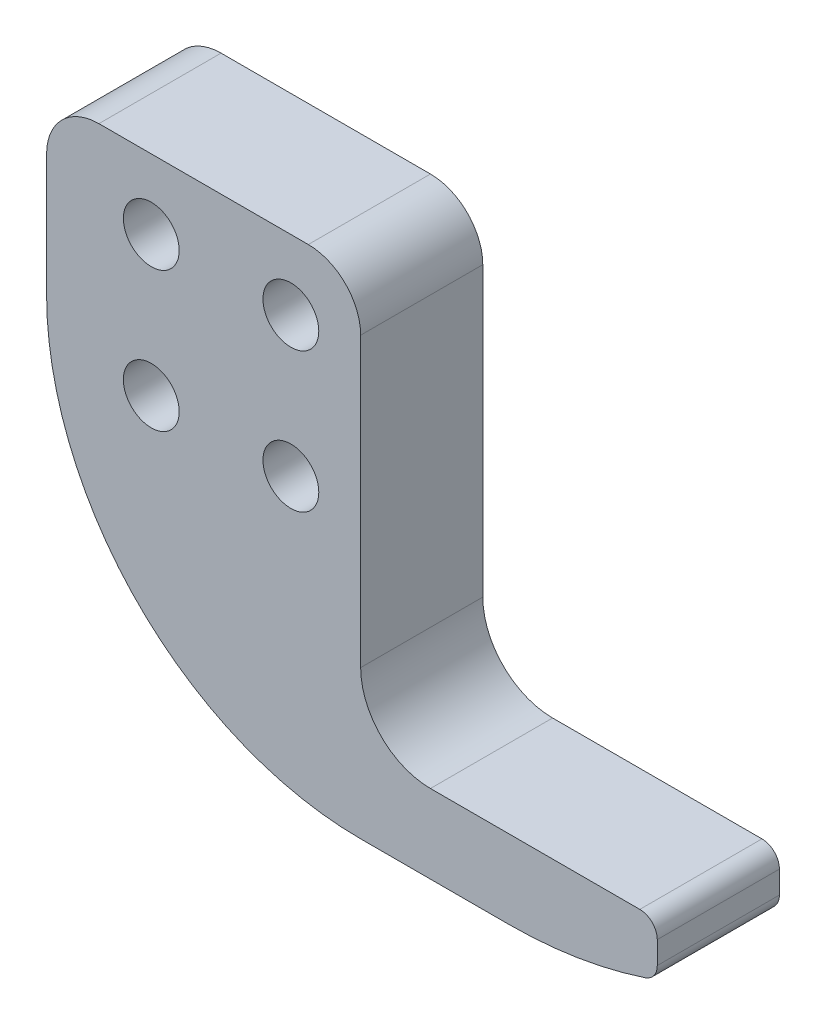
SolidWorks part; units mm, degrees
material "光敏树脂"
ref_plane "前视基准面" through (0, 0, 0) normal (0, 0, 1) x (1, 0, 0)
ref_plane "上视基准面" through (0, 0, 0) normal (0, 1, 0) x (1, 0, 0)
ref_plane "右视基准面" through (0, 0, 0) normal (1, 0, 0) x (0, 0, -1)
sketch "草图1" plane through (0, 0, 0) normal (0, 0, 1) x (1, 0, 0)
  line L0 (-139.1546, 76.5) -> (-139.1546, -33.6254) construction
  line L1 (-91.6495, 50) -> (0, 50) construction
  line L2 (-90.2793, 53) -> (-5.3283, 53) construction
  line L4 (-99.1546, 26.5) -> (0, 26.5) construction
  line L6 (-99.1546, 26.5) -> (-88, 26.5) construction
  line L7 (0, 26.5) -> (0, 0) construction
  line L8 (-88, 26.5) -> (-88, -20.8435) construction
  arc A0 (-139.1546, 66.5) -> (-99.1546, 26.5) centre (-99.1546, 66.5) ccw
  dimension "D1" = 3
  dimension "D4" = 80
  dimension "D3" = 23.5
  dimension "D7" = 10
  dimension "D8" = 88
  dimension "D9" = 11.1546
sketch "草图2" plane through (0, 0, 0) normal (0, 0, 1) x (1, 0, 0)
  line L0 (0, 0) -> (-88, 0) construction
  line L1 (-88, 26.5) -> (-88, -20.8435) construction
  line L2 (0, 3) -> (-88, 3) construction
  line L3 (-99.1546, 26.5) -> (0, 26.5) construction
  line L4 (-139.1546, 76.5) -> (-139.1546, -33.6254) construction
  line L5 (-99.1546, 26.5) -> (-88, 26.5) construction
  line L6 (-139.1546, 76.5) -> (-139.1546, 66.5) construction
  line L7 (-88, 3) -> (-88, 26.5) construction
  line L8 (-161.1546, 76.5) -> (-161.1546, 66.5) construction
  line L9 (-99.1546, 4.5) -> (-88, 4.5) construction
  line L10 (-117.1546, 76.5) -> (-117.1546, 66.5)
  line L11 (-99.1546, 48.5) -> (-82.1546, 48.5)
  line L12 (-117.1546, 76.5) -> (-99.1546, 76.5)
  line L13 (-162.1546, 76.5) -> (-162.1546, 66.5) construction
  line L14 (-99.1546, 3.5) -> (-88, 3.5) construction
  line L15 (-164.6546, 76.5) -> (-164.6546, 66.5) construction
  line L16 (-99.1546, 1) -> (-88, 1) construction
  line L17 (-169.1546, 76.5) -> (-169.1546, 66.5) construction
  line L18 (-99.1546, -3.5) -> (-88, -3.5) construction
  line L19 (-177.1546, 76.5) -> (-177.1546, 66.5) construction
  line L20 (-99.1546, -11.5) -> (-88, -11.5) construction
  line L21 (-177.1546, 76.5) -> (-162.1546, 76.5) construction
  line L22 (-88, 3.5) -> (-88, -11.5) construction
  line L23 (-99.1546, 66.5) -> (-99.1546, 1) construction
  line L24 (-99.1546, 66.5) -> (-106.9101, 1.4608) construction
  line L25 (-164.6546, 75.2931) -> (-164.6546, 78.7931) construction
  line L26 (-99.1546, 66.5) -> (-99.1546, 1) construction
  line L27 (-99.1546, 66.5) -> (-106.9101, 1.4608) construction
  line L28 (-99.1546, 76.5) -> (-99.1546, 53)
  line L29 (-99.1546, 53) -> (-82.1546, 53)
  line L30 (-99.1546, 48.5) -> (-88, 48.5) construction
  line L31 (-82.1546, 53) -> (-82.1546, 48.5)
  line L32 (-90.2793, 53) -> (-5.3283, 53) construction
  arc A0 (-139.1546, 66.5) -> (-99.1546, 26.5) centre (-99.1546, 66.5) ccw construction
  arc A1 (-139.1546, 66.5) -> (-99.1546, 26.5) centre (-99.1546, 66.5) ccw construction
  arc A2 (-161.1546, 66.5) -> (-99.1546, 4.5) centre (-99.1546, 66.5) ccw construction
  arc A3 (-117.1546, 66.5) -> (-99.1546, 48.5) centre (-99.1546, 66.5) ccw
  arc A4 (-162.1546, 66.5) -> (-99.1546, 3.5) centre (-99.1546, 66.5) ccw construction
  arc A5 (-164.6546, 66.5) -> (-99.1546, 1) centre (-99.1546, 66.5) ccw construction
  arc A6 (-169.1546, 66.5) -> (-99.1546, -3.5) centre (-99.1546, 66.5) ccw construction
  arc A7 (-177.1546, 66.5) -> (-99.1546, -11.5) centre (-99.1546, 66.5) ccw construction
  circle A8 centre (-91.7546, 1) radius 3.5 construction
  circle A9 centre (-99.1546, 1) radius 3.5 construction
  circle A10 centre (-106.9101, 1.4608) radius 3.5 construction
  circle A11 centre (-114.5564, 2.8366) radius 3.5 construction
  circle A12 centre (-121.9861, 5.108) radius 3.5 construction
  circle A13 centre (-129.0945, 8.2432) radius 3.5 construction
  circle A14 centre (-135.7817, 12.198) radius 3.5 construction
  circle A15 centre (-141.9536, 16.9168) radius 3.5 construction
  circle A16 centre (-147.5234, 22.3332) radius 3.5 construction
  circle A17 centre (-152.4127, 28.3709) radius 3.5 construction
  circle A18 centre (-156.5527, 34.9451) radius 3.5 construction
  circle A19 centre (-159.8851, 41.9633) radius 3.5 construction
  circle A20 centre (-162.3632, 49.3266) radius 3.5 construction
  circle A21 centre (-163.9519, 56.9316) radius 3.5 construction
  circle A22 centre (-164.6291, 64.6711) radius 3.5 construction
  circle A23 centre (-164.6546, 72.3711) radius 3.5 construction
  arc A24 (-139.1546, 66.5) -> (-99.1546, 26.5) centre (-99.1546, 66.5) ccw construction
  circle A26 centre (-91.7546, 1) radius 1.6 construction
  circle A27 centre (-99.1546, 1) radius 1.6 construction
  circle A28 centre (-106.9101, 1.4608) radius 1.6 construction
  circle A29 centre (-114.5564, 2.8366) radius 1.6 construction
  circle A30 centre (-121.9861, 5.108) radius 1.6 construction
  circle A31 centre (-129.0945, 8.2432) radius 1.6 construction
  circle A32 centre (-135.7817, 12.198) radius 1.6 construction
  circle A33 centre (-141.9536, 16.9168) radius 1.6 construction
  circle A34 centre (-147.5234, 22.3332) radius 1.6 construction
  circle A35 centre (-152.4127, 28.3709) radius 1.6 construction
  circle A36 centre (-156.5527, 34.9451) radius 1.6 construction
  circle A37 centre (-159.8851, 41.9633) radius 1.6 construction
  circle A38 centre (-162.3632, 49.3266) radius 1.6 construction
  circle A39 centre (-163.9519, 56.9316) radius 1.6 construction
  circle A40 centre (-164.6291, 64.6711) radius 1.6 construction
  circle A41 centre (-164.6546, 72.3711) radius 1.6 construction
  dimension "D8" = 7
  dimension "D9" = 7
  dimension "D10" = 7.4
  dimension "D13" = 7
  dimension "D16" = 3.2
  dimension "D17" = 3.2
  dimension "D20" = 3.2
  dimension "D1" = 3
  dimension "D2" = 22
  dimension "D4" = 1
  dimension "D12" = 6.8
  dimension "D14" = 7.7691
  dimension "D15" = 7.7
  dimension "D19" = 6.8
  dimension "D21" = 57
  dimension "D3" = 22
  dimension "D5" = 3.5
  dimension "D6" = 7
  dimension "D7" = 8
  dimension "D11" = 14
  dimension "D18" = 14
extrude "凸台-拉伸1" add sketch "草图2" along normal mid plane 7 contours L28 L29 L31 L11 A3 L10 L12
sketch "草图3" plane through (0, 0, 3.5) normal (0, 0, 1) x (1, 0, 0)
  line L0 (-99.1546, 76.5) -> (-99.1546, 53) construction
  line L1 (-111.1546, 64.5) -> (-103.1546, 64.5) construction
  line L2 (-111.1546, 64.5) -> (-111.1546, 72.5) construction
  line L3 (-111.1546, 72.5) -> (-103.1546, 72.5) construction
  line L4 (-103.1546, 64.5) -> (-103.1546, 72.5) construction
  line L5 (-111.1546, 64.5) -> (-103.1546, 72.5) construction
  line L6 (-111.1546, 72.5) -> (-103.1546, 64.5) construction
  line L8 (-117.1546, 76.5) -> (-99.1546, 76.5) construction
  line L9 (-128.5975, 61) -> (-114.0101, 61) construction
  line L10 (-114.0101, 61) -> (-114.0101, 53) construction
  line L11 (-114.0101, 53) -> (-128.5975, 53) construction
  line L13 (-90.2793, 53) -> (-5.3283, 53) construction
  line L14 (-114.0101, 57) -> (-138.0101, 57) construction
  circle A0 centre (-103.1546, 72.5) radius 1.6
  circle A1 centre (-111.1546, 72.5) radius 1.6
  circle A2 centre (-111.1546, 64.5) radius 1.6
  circle A3 centre (-103.1546, 64.5) radius 1.6
  arc A4 (-139.1546, 66.5) -> (-99.1546, 26.5) centre (-99.1546, 66.5) ccw construction
  circle A5 centre (-111.1546, 64.5) radius 3 construction
  point P2 (-107.1546, 68.5)
  dimension "D1" = 3.2
  dimension "D6" = 3.2
  dimension "D7" = 3.2
  dimension "D8" = 3.2
  dimension "D11" = 6
  dimension "D2" = 4
  dimension "D3" = 8
  dimension "D4" = 4
  dimension "D5" = 8
  dimension "D9" = 8
  dimension "D10" = 24
extrude "切除-拉伸1" cut sketch "草图3" against normal blind 16
sketch "草图4" plane through (0, 0, 3.5) normal (0, 0, 1) x (1, 0, 0)
  line L0 (-87.4594, 50) -> (-82.1546, 50) construction
  line L1 (-91.6495, 50) -> (0, 50) construction
  line L2 (-82.1546, 53) -> (-82.1546, 48.5) construction
  line L3 (-99.1546, 48.5) -> (-82.1546, 48.5) construction
  line L4 (-90.684, 48.5) -> (-90.684, 46.6274)
  line L5 (-90.684, 46.6274) -> (-65.684, 46.6274)
  line L6 (-65.684, 46.6274) -> (-65.684, 73.5)
  arc A0 (-90.684, 48.5) -> (-65.684, 73.5) centre (-90.684, 73.5) ccw
  dimension "D1" = 50
extrude "切除-拉伸2" cut sketch "草图4" against normal blind 13
fillet "圆角1" radius 1 2 edges at (-82.1546, 53, 0) (-82.1546, 50, 0)
fillet "圆角2" radius 3 2 edges at (-99.1546, 76.5, 0) (-117.1546, 76.5, 0)
fillet "圆角3" radius 4 1 edges at (-99.1546, 53, 0)
